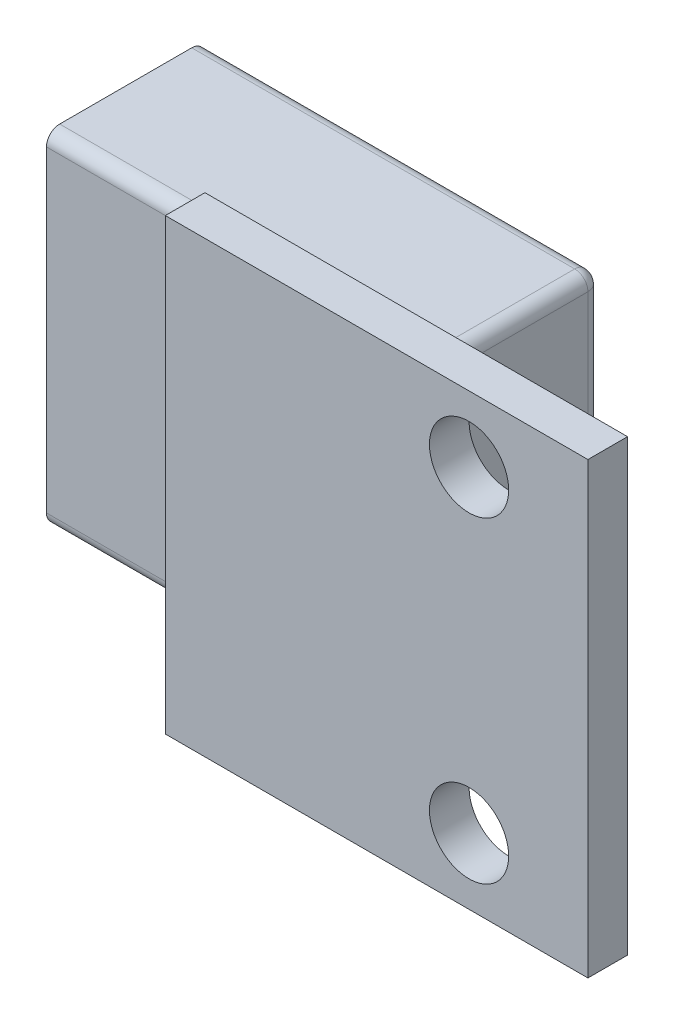
SolidWorks part; units mm, degrees
ref_plane "Front Plane" through (0, 0, 0) normal (0, 0, 1) x (1, 0, 0)
ref_plane "Top Plane" through (0, 0, 0) normal (0, 1, 0) x (1, 0, 0)
ref_plane "Right Plane" through (0, 0, 0) normal (1, 0, 0) x (0, 0, -1)
sketch "Sketch1" plane through (0, 0, 0) normal (0, 0, 1) x (1, 0, 0)
  line L1 (-8, -8.5) -> (8, -8.5)
  line L2 (-8, -8.5) -> (-8, 8.5)
  line L3 (-8, 8.5) -> (8, 8.5)
  line L4 (8, -8.5) -> (8, 8.5)
  line L5 (-8, -8.5) -> (8, 8.5) construction
  line L6 (-8, 8.5) -> (8, -8.5) construction
  point P0 (0, 0)
  dimension "D1" = 17
  dimension "D2" = 16
extrude "Boss-Extrude1" add sketch "Sketch1" along normal blind 1.5
sketch "Sketch2" plane through (0, 0, 0) normal (0, 1, 0) x (1, 0, 0)
  line L0 (-5, 0) -> (-5, 1)
  line L1 (8, 0) -> (-8, 0) construction
  line L2 (-5, 1) -> (-15, 1)
  line L3 (-15, 1) -> (-15, 7)
  line L4 (-15, 7) -> (0, 7)
  line L5 (0, 7) -> (0, 0)
  line L6 (0, 0) -> (-5, 0)
  line L7 (-8, -1.5) -> (-8, 0) construction
  dimension "D1" = 3
  dimension "D2" = 5
  dimension "D3" = 15
  dimension "D4" = 1
  dimension "D5" = 6
extrude "Boss-Extrude2" add sketch "Sketch2" along normal mid plane 13
sketch "Sketch3" plane through (-15, 0, 0) normal (-1, 0, 0) x (0, 0, 1)
  line L0 (-6.7, 6.2) -> (-6.7, -6.2)
  line L1 (-6, -5) -> (-4, -5)
  line L2 (-6, -5) -> (-6, 5)
  line L3 (-6, 5) -> (-4, 5)
  line L4 (-4, -5) -> (-4, 5)
  line L5 (-6, -5) -> (-4, 5) construction
  line L6 (-6, 5) -> (-4, -5) construction
  line L7 (-6.7, -6.2) -> (-1.3, -6.2)
  line L8 (-1.3, -6.2) -> (-1.3, 6.2)
  line L9 (-1.3, 6.2) -> (-6.7, 6.2)
  point P0 (-5, 0)
  point P5 (0, 0)
  dimension "D1" = 5
  dimension "D2" = 2
  dimension "D3" = 10
extrude "Cut-Extrude1" cut sketch "Sketch3" against normal blind 10
fillet "Fillet1" radius 0.5 8 edges at (-10, 6.2, -1.3) (-10, -6.2, -1.3) (-10, 6.2, -6.7) (-10, -6.2, -6.7) (-7.5, -6.5, -7) (-10, 6.5, -1) (-10, -6.5, -1) (-7.5, 6.5, -7)
fillet "Fillet2" radius 0.5 5 edges at (0, 6.5, -3.25) (0, 6.3536, -6.8536) (0, -6.5, -3.25) (0, -6.3536, -6.8536) (0, 0, -7)
chamfer "Chamfer1" distance 0.2 angle 45 8 edges at (-15, -5, -5) (-10, -5, -4) (-15, 0, -4) (-10, 5, -4) (-15, 5, -5) (-10, 5, -6) (-15, 0, -6) (-10, -5, -6)
sketch "Sketch4" plane through (0, 0, 0) normal (0, 0, -1) x (-1, 0, 0)
  line L0 (0, 0) -> (-11.1066, 0) construction
  line L1 (8, 8.5) -> (8, -8.5) construction
  circle A0 centre (-3.5, 6) radius 1.5
  circle A1 centre (-3.5, -6) radius 1.5
  point P7 (0, 0)
  point P9 (-3.3726, 5.4434)
  dimension "D3" = 3
  dimension "D1" = 11.5
  dimension "D2" = 6
extrude "Cut-Extrude2" cut sketch "Sketch4" against normal blind 10
